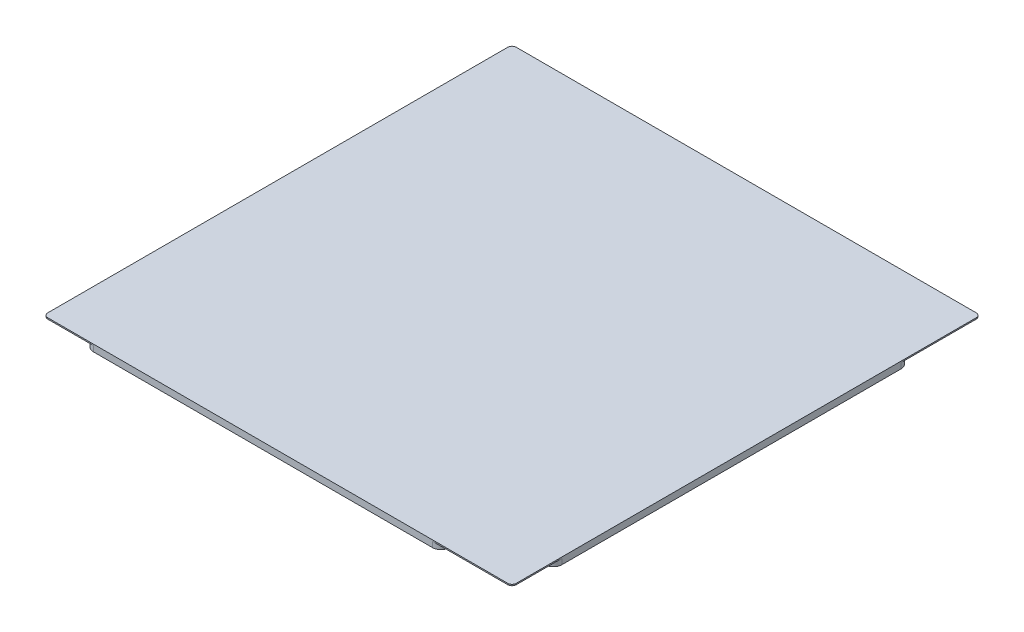
SolidWorks part; units mm, degrees
material "Kapton"
ref_plane "Front Plane" through (0, 0, 0) normal (0, 0, 1) x (1, 0, 0)
ref_plane "Top Plane" through (0, 0, 0) normal (0, 1, 0) x (1, 0, 0)
ref_plane "Right Plane" through (0, 0, 0) normal (1, 0, 0) x (0, 0, -1)
sketch "Sketch1" plane through (0, 0, 0) normal (0, 1, 0) x (1, 0, 0)
  line L1 (-55.5, -55.5) -> (55.5, -55.5)
  line L2 (-55.5, -55.5) -> (-55.5, 55.5)
  line L3 (-55.5, 55.5) -> (55.5, 55.5)
  line L4 (55.5, -55.5) -> (55.5, 55.5)
  line L5 (-55.5, -55.5) -> (55.5, 55.5) construction
  line L6 (-55.5, 55.5) -> (55.5, -55.5) construction
  point P0 (0, 0)
  dimension "D1" = 111
extrude "Boss-Extrude1" add sketch "Sketch1" along normal mid plane 0.3
sketch "Sketch2" plane through (0, -0.15, 0) normal (0, -1, 0) x (1, 0, 0)
  line L0 (57, -55.5) -> (35.6667, -55.5) construction
  line L1 (55.5, -55.5) -> (-55.5, -55.5) construction
  line L2 (35.6667, -55.5) -> (10.6667, -55.5) construction
  line L3 (10.6667, -55.5) -> (-10.6667, -55.5) construction
  line L4 (-10.6667, -55.5) -> (-35.6667, -55.5) construction
  line L5 (-35.6667, -55.5) -> (-57, -55.5) construction
  line L6 (35.6667, -55.5) -> (45.6667, -42) construction
  line L7 (-55.5, -55.5) -> (-55.5, 55.5) construction
  line L8 (55.5, 55.5) -> (55.5, -55.5) construction
  line L9 (-42, -45.6667) -> (-55.5, -45.6667)
  line L10 (45.6667, -42) -> (-38.6667, -42)
  line L11 (45.6667, -42) -> (45.6667, -55.5)
  line L12 (45.6667, -55.5) -> (-38.6667, -55.5)
  line L13 (-38.6667, -42) -> (-38.6667, -55.5)
  line L14 (-42, -45.6667) -> (-42, 38.6667)
  line L15 (-42, 38.6667) -> (-55.5, 38.6667)
  line L16 (-55.5, -45.6667) -> (-55.5, 38.6667)
  line L17 (-45.6667, 42) -> (-45.6667, 55.5)
  line L18 (-45.6667, 42) -> (38.6667, 42)
  line L19 (38.6667, 42) -> (38.6667, 55.5)
  line L20 (-45.6667, 55.5) -> (38.6667, 55.5)
  line L21 (42, 45.6667) -> (55.5, 45.6667)
  line L22 (42, 45.6667) -> (42, -38.6667)
  line L23 (42, -38.6667) -> (55.5, -38.6667)
  line L24 (55.5, 45.6667) -> (55.5, -38.6667)
  line L25 (-55.5, 55.5) -> (55.5, 55.5) construction
  point P33 (0, 0)
  dimension "D1" = 25
  dimension "D2" = 13.5
  dimension "D3" = 10
  dimension "D4" = 1.5
  dimension "D5" = 1.5
  dimension "D6" = 3
  dimension "D7" = 4
extrude "Boss-Extrude2" add sketch "Sketch2" along normal blind 1.3
fillet "Fillet1" radius 2 16 edges at (45.6667, -0.8, -42) (-38.6667, -0.8, -42) (-38.6667, -0.8, -55.5) (-55.5, -0.8, -45.6667) (-42, -0.8, -45.6667) (-42, -0.8, 38.6667) (-55.5, -0.8, 38.6667) (-45.6667, -0.8, 55.5) (-45.6667, -0.8, 42) (38.6667, -0.8, 42) (38.6667, -0.8, 55.5) (45.6667, -0.8, -55.5) (42, -0.8, 45.6667) (55.5, -0.8, 45.6667) (55.5, -0.8, -38.6667) (42, -0.8, -38.6667)
fillet "Fillet2" radius 1 4 edges at (-55.5, 0, 55.5) (-55.5, 0, -55.5) (55.5, 0, -55.5) (55.5, 0, 55.5)
equation "\"panel_width\"= 114mm"
equation "\"finger_joint_width\" = 25mm"
equation "\"D1@Sketch1\"=\"panel_width\"-3"
equation "\"D1@Sketch2\"=\"finger_joint_width\""
